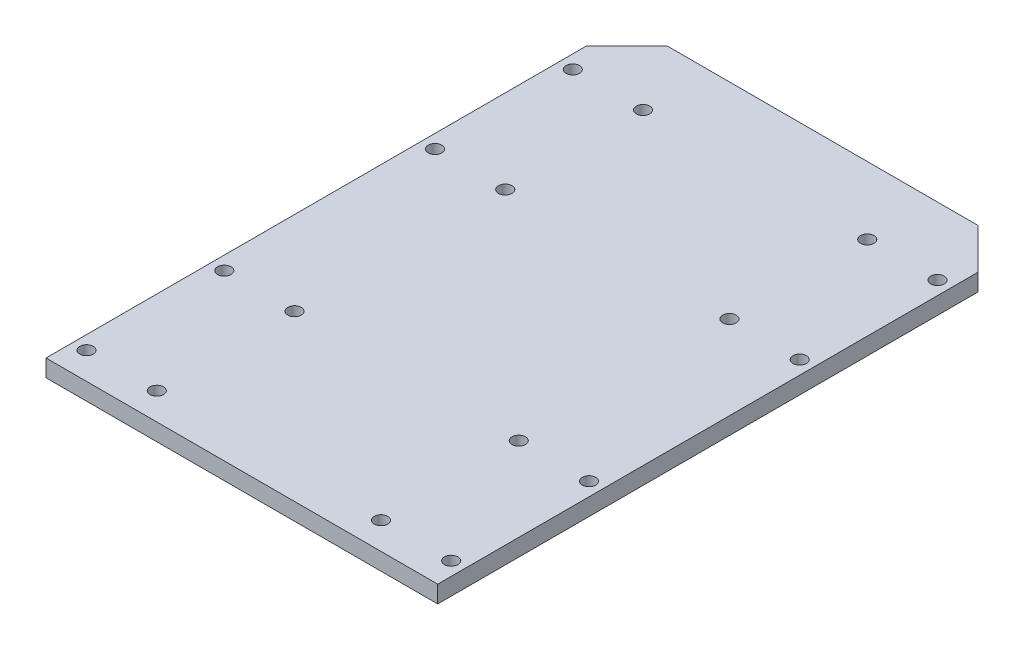
SolidWorks part; units mm, degrees
ref_plane "Front Plane" through (0, 0, 0) normal (0, 0, 1) x (1, 0, 0)
ref_plane "Top Plane" through (0, 0, 0) normal (0, 1, 0) x (1, 0, 0)
ref_plane "Right Plane" through (0, 0, 0) normal (1, 0, 0) x (0, 0, -1)
sketch "Sketch1" plane through (0, 0, 0) normal (0, 1, 0) x (1, 0, 0)
  line L0 (-145, 200) -> (-130, 215)
  line L1 (0, 0) -> (-145, 0)
  line L2 (0, 0) -> (0, 200)
  line L3 (0, 200) -> (-145, 200)
  line L4 (-145, 0) -> (-145, 200)
  line L5 (-130, 215) -> (-15, 215)
  line L6 (-15, 215) -> (0, 200)
  line L7 (-140, 190) -> (-114, 190) construction
  line L8 (-140, 139) -> (-114, 139) construction
  line L9 (-140, 190) -> (-140, 139) construction
  line L10 (-140, 190) -> (-145, 190) construction
  line L11 (-72.5, 200) -> (-72.5, 0) construction
  line L12 (-145, 100) -> (0, 100) construction
  circle A0 centre (-140, 190) radius 2.5
  circle A1 centre (-114, 190) radius 2.5
  circle A2 centre (-140, 139) radius 2.5
  circle A3 centre (-114, 139) radius 2.5
  circle A4 centre (-31, 190) radius 2.5
  circle A5 centre (-5, 190) radius 2.5
  circle A6 centre (-5, 139) radius 2.5
  circle A7 centre (-31, 139) radius 2.5
  circle A8 centre (-5, 10) radius 2.5
  circle A9 centre (-5, 61) radius 2.5
  circle A10 centre (-31, 61) radius 2.5
  circle A11 centre (-31, 10) radius 2.5
  circle A12 centre (-114, 10) radius 2.5
  circle A13 centre (-114, 61) radius 2.5
  circle A14 centre (-140, 10) radius 2.5
  circle A15 centre (-140, 61) radius 2.5
  dimension "D9" = 5
  dimension "D1" = 45
  dimension "D2" = 15
  dimension "D3" = 200
  dimension "D4" = 145
  dimension "D5" = 51
  dimension "D6" = 26
  dimension "D7" = 5
  dimension "D8" = 10
extrude "Boss-Extrude1" add sketch "Sketch1" along normal blind 6.35 contours L4 L1 L2 L3 | L6 L5 L0 L3
